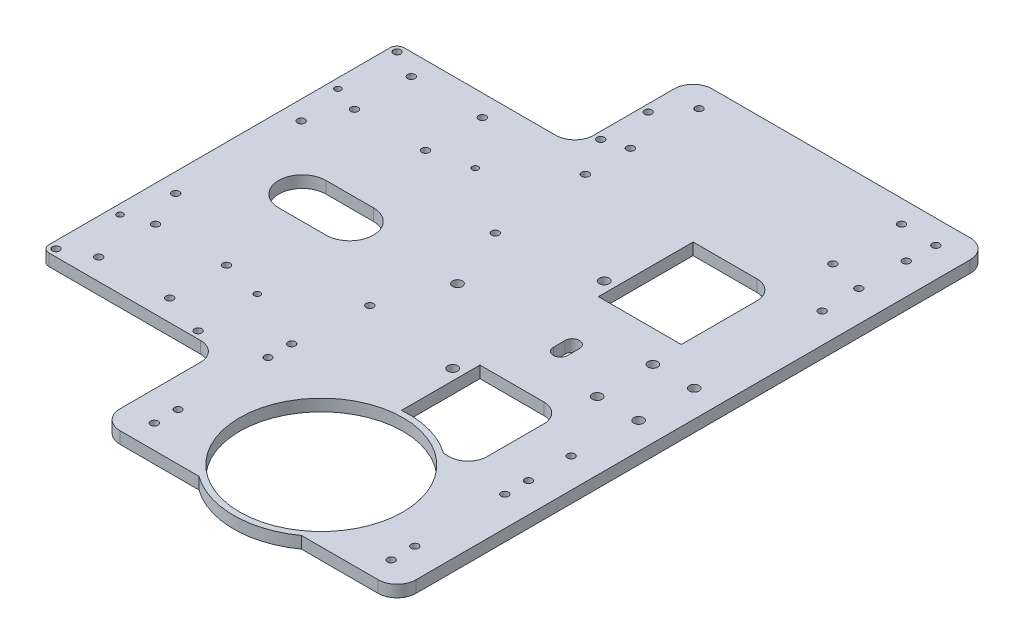
SolidWorks part; units mm, degrees
material "Thornel Mat VMA"
ref_plane "前视基准面" through (0, 0, 0) normal (0, 0, 1) x (1, 0, 0)
ref_plane "上视基准面" through (0, 0, 0) normal (0, 1, 0) x (1, 0, 0)
ref_plane "右视基准面" through (0, 0, 0) normal (1, 0, 0) x (0, 0, -1)
sketch "草图1" plane through (0, 0, 0) normal (0, 1, 0) x (1, 0, 0)
  line L1 (-100, 125) -> (100, 125)
  line L2 (-100, 125) -> (-100, -125)
  line L3 (-100, -125) -> (100, -125)
  line L4 (100, 125) -> (100, -125)
  line L5 (-100, 125) -> (100, -125) construction
  line L6 (-100, -125) -> (100, 125) construction
  point P0 (0, 0)
  dimension "D1" = 200
  dimension "D2" = 250
extrude "凸台-拉伸1" add sketch "草图1" along normal blind 5
ref_plane "基准面1" through (0, 5, 0) normal (0, 1, 0) x (1, 0, 0)
sketch "草图2" plane through (0, 5, 0) normal (0, 1, 0) x (1, 0, 0)
  line L0 (-100, 0) -> (100, 0) construction
  line L1 (-175, 175) -> (-25, 175)
  line L2 (-175, 175) -> (-175, 75)
  line L3 (-175, 75) -> (-25, 75)
  line L4 (-25, 175) -> (-25, 75)
  line L5 (-175, 175) -> (-25, 75) construction
  line L6 (-175, 75) -> (-25, 175) construction
  line L7 (-100, 125) -> (-100, -125) construction
  line L8 (100, -125) -> (100, 125) construction
  line L9 (-175, -75) -> (-25, -75)
  line L10 (-25, -175) -> (-25, -75)
  line L11 (-175, -175) -> (-25, -175)
  line L12 (-175, -175) -> (-175, -75)
  point P0 (-100, 125)
  dimension "D1" = 100
  dimension "D2" = 150
extrude "切除-拉伸1" cut sketch "草图2" against normal blind 10
ref_plane "基准面2" through (0, 5, 0) normal (0, 1, 0) x (1, 0, 0)
ref_plane "基准面3" through (0, 0, 0) normal (0, -1, 0) x (-1, 0, 0)
sketch "草图3" plane through (0, 0, 0) normal (0, -1, 0) x (-1, 0, 0)
  circle A0 centre (85, 66) radius 1.55
  circle A1 centre (55, 66) radius 1.55
  circle A2 centre (55, 42) radius 1.55
  circle A3 centre (85, 42) radius 1.55
  circle A4 centre (55, -42) radius 1.55
  circle A5 centre (85, -42) radius 1.55
  circle A6 centre (55, -66) radius 1.55
  circle A7 centre (85, -66) radius 1.55
extrude "切除-拉伸2" cut sketch "草图3" against normal blind 10
ref_plane "基准面4" through (0, 5, 0) normal (0, 1, 0) x (1, 0, 0)
sketch "草图5" plane through (0, 5, 0) normal (0, 1, 0) x (1, 0, 0)
  line L0 (-70, 97) -> (146, -97) construction
  line L1 (-67.5, 97) -> (-72.5, 97) construction
  line L2 (143.5, -97) -> (148.5, -97) construction
  line L3 (38, 0) -> (-100, 0) construction
  line L4 (-100, 75) -> (-100, -75) construction
ref_plane "基准面5" through (0, 0, 0) normal (0, -1, 0) x (-1, 0, 0)
sketch "草图6" plane through (0, 0, 0) normal (0, -1, 0) x (-1, 0, 0)
  line L5 (-38, 0) -> (100, 0) construction
  line L16 (25, -125) -> (25, -75) construction
  line L17 (-35, -25) -> (-70, -25)
  line L18 (-35, -25) -> (-35, -65)
  line L19 (-35, -65) -> (-70, -65)
  line L20 (-70, -25) -> (-70, -65)
  line L21 (25, -125) -> (-100, -125) construction
  line L22 (-35, 25) -> (-70, 25)
  line L23 (-35, 25) -> (-35, 65)
  line L24 (-35, 65) -> (-70, 65)
  line L25 (-70, 25) -> (-70, 65)
  circle A0 centre (-30.5, 32) radius 2.05
  circle A1 centre (-0.5, 0) radius 2.05
  circle A2 centre (-30.5, -32) radius 2.05
  dimension "D1" = 4.1
  dimension "D2" = 4.1
  dimension "D3" = 4.1
  dimension "D4" = 40
  dimension "D5" = 35
  dimension "D6" = 60
  dimension "D7" = 60
extrude "切除-拉伸3" cut sketch "草图6" against normal blind 5 and the other way blind 10
sketch "草图7" plane through (0, 0, 0) normal (0, -1, 0) x (-1, 0, 0)
  line L0 (-38, 0) -> (-38, -125) construction
  line L1 (70, 97) -> (-146, -97) construction
  line L2 (25, -125) -> (-100, -125) construction
  circle A0 centre (-38, -95) radius 35
  dimension "D1" = 70
  dimension "D2" = 30
extrude "切除-拉伸4" cut sketch "草图7" against normal blind 5
ref_plane "基准面6" through (0, 5, 0) normal (0, 1, 0) x (1, 0, 0)
sketch "草图8" plane through (0, 5, 0) normal (0, 1, 0) x (1, 0, 0)
  circle A0 centre (71.25, 11.75) radius 2.05
  circle A1 centre (88.75, 11.75) radius 2.05
  circle A2 centre (88.75, -11.75) radius 2.05
  circle A3 centre (71.25, -11.75) radius 2.05
extrude "切除-拉伸5" cut sketch "草图8" against normal through all
sketch "草图9" plane through (0, 5, 0) normal (0, 1, 0) x (1, 0, 0)
  circle A0 centre (38, -95) radius 53.0754 construction
sketch "草图10" plane through (0, 5, 0) normal (0, 1, 0) x (1, 0, 0)
  line L0 (-25, -60) -> (100, -60) construction
  line L1 (100, -125) -> (100, 125) construction
  line L2 (-25, -60) -> (-25, -125) construction
  line L4 (-12.5, -67) -> (87.5, -67) construction
  line L5 (-12.5, -67) -> (-12.5, -115) construction
  line L6 (-12.5, -115) -> (87.5, -115) construction
  line L7 (87.5, -67) -> (87.5, -115) construction
  arc A0 (35, -60.1288) -> (19.9722, -125) centre (38, -95) ccw construction
  circle A1 centre (-12.5, -67) radius 1.55
  circle A2 centre (-12.5, -115) radius 1.55
  circle A3 centre (87.5, -67) radius 1.55
  circle A4 centre (87.5, -115) radius 1.55
  dimension "D3" = 3.1
  dimension "D4" = 3.1
  dimension "D5" = 7
  dimension "D2" = 3.1
  dimension "D8" = 3.1
  dimension "D1" = 12.5
  dimension "D6" = 100
  dimension "D7" = 48
extrude "切除-拉伸6" cut sketch "草图10" against normal blind 10
sketch "草图11" plane through (0, 5, 0) normal (0, 1, 0) x (1, 0, 0)
  line L0 (100, -125) -> (100, 125) construction
  line L1 (87.5, 115) -> (-12.5, 115) construction
  line L2 (87.5, 115) -> (87.5, 67) construction
  line L3 (87.5, 67) -> (-12.5, 67) construction
  line L4 (-12.5, 115) -> (-12.5, 67) construction
  line L5 (100, 125) -> (-25, 125) construction
  circle A0 centre (87.5, 115) radius 1.55
  circle A1 centre (87.5, 67) radius 1.55
  circle A2 centre (-12.5, 115) radius 1.55
  circle A3 centre (-12.5, 67) radius 1.55
  dimension "D2" = 3.1
  dimension "D3" = 3.1
  dimension "D4" = 3.1
  dimension "D5" = 3.1
  dimension "D1" = 100
  dimension "D6" = 12.5
  dimension "D7" = 10
extrude "切除-拉伸7" cut sketch "草图11" against normal blind 5
sketch "草图14" plane through (0, 5, 0) normal (0, 1, 0) x (1, 0, 0)
  line L0 (38, 0) -> (-100, 0) construction
  line L1 (-92, 26.5) -> (-10, 26.5) construction
  line L2 (-92, 26.5) -> (-92, -26.5) construction
  line L3 (-92, -26.5) -> (-10, -26.5) construction
  line L4 (-10, 26.5) -> (-10, -26.5) construction
  line L5 (-92, 26.5) -> (-10, -26.5) construction
  line L6 (-92, -26.5) -> (-10, 26.5) construction
  line L7 (-100, 75) -> (-100, -75) construction
  circle A0 centre (-92, -26.5) radius 1.55
  circle A1 centre (-92, 26.5) radius 1.55
  circle A2 centre (-10, 26.5) radius 1.55
  circle A3 centre (-10, -26.5) radius 1.55
  point P0 (-51, 0)
  dimension "D4" = 3.1
  dimension "D5" = 3.1
  dimension "D6" = 3.1
  dimension "D7" = 3.1
  dimension "D1" = 53
  dimension "D2" = 82
  dimension "D3" = 90
extrude "切除-拉伸10" cut sketch "草图14" against normal blind 5
sketch "草图16" plane through (0, 5, 0) normal (0, 1, 0) x (1, 0, 0)
  line L0 (38, 0) -> (-100, 0) construction
  line L1 (-96, 46) -> (-38, 46) construction
  line L2 (-96, 46) -> (-96, -46) construction
  line L3 (-96, -46) -> (-38, -46) construction
  line L4 (-38, 46) -> (-38, -46) construction
  line L5 (-96, 46) -> (-38, -46) construction
  line L6 (-96, -46) -> (-38, 46) construction
  line L7 (-100, 75) -> (-100, -75) construction
  circle A0 centre (-96, 46) radius 1.3
  circle A1 centre (-38, 46) radius 1.3
  circle A2 centre (-38, -46) radius 1.3
  circle A3 centre (-96, -46) radius 1.3
  point P0 (-67, 0)
  dimension "D4" = 2.6
  dimension "D5" = 2.6
  dimension "D6" = 2.6
  dimension "D7" = 2.6
  dimension "D1" = 58
  dimension "D2" = 92
  dimension "D3" = 4
extrude "切除-拉伸11" cut sketch "草图16" against normal blind 5
sketch "草图18" plane through (0, 5, 0) normal (0, 1, 0) x (1, 0, 0)
  line L0 (35, -58.1218) -> (35, -60.1288)
  line L1 (35, -60.1288) -> (35, -25) construction
  line L2 (56.0278, -65) -> (59.8008, -65.1048)
  circle A0 centre (38, -95) radius 34.5
  circle A1 centre (38, -95) radius 37
  dimension "D1" = 74
extrude "凸台-拉伸2" add sketch "草图18" against normal blind 5 contours L2 A1 L0 A0
fillet "圆角1" radius 8 3 edges at (70, 2.5, -65) (70, 2.5, 65) (70, 2.5, 25)
sketch "草图19" plane through (0, 5, 0) normal (0, 1, 0) x (1, 0, 0)
  line L0 (-100, 75) -> (-25, 75) construction
  line L1 (-100, 75) -> (-100, -75) construction
  line L2 (-25, -75) -> (-100, -75) construction
  circle A0 centre (-97, 72) radius 1.55
  circle A1 centre (-97, -72) radius 1.55
  dimension "D1" = 3.1
  dimension "D2" = 3
  dimension "D3" = 3
  dimension "D4" = 3.1
  dimension "D6" = 3
  dimension "D5" = 3
extrude "切除-拉伸12" cut sketch "草图19" against normal blind 10
sketch "草图20" plane through (0, 5, 0) normal (0, 1, 0) x (1, 0, 0)
  line L0 (-25, 75) -> (-25, 125) construction
  line L1 (100, 125) -> (-25, 125) construction
  line L2 (100, -125) -> (100, 125) construction
  circle A0 centre (72.4985, 115.5) radius 1.55
  circle A1 centre (72.5, 86.5) radius 1.55
  circle A2 centre (87, 103) radius 1.55
  circle A3 centre (87, 83) radius 1.55
  circle A4 centre (-22, 103) radius 1.55
  circle A5 centre (-22, 83) radius 1.55
  circle A6 centre (-12.5, 86) radius 1.55
  circle A7 centre (-12.5, 115) radius 1.55 construction
  dimension "D1" = 3.1
  dimension "D2" = 3.1
  dimension "D3" = 3.1
  dimension "D4" = 3.1
  dimension "D5" = 3.1
  dimension "D6" = 3.1
  dimension "D7" = 3.1
  dimension "D8" = 12.5
  dimension "D9" = 29
  dimension "D10" = 3
  dimension "D11" = 22
  dimension "D12" = 3
  dimension "D13" = 20
  dimension "D14" = 13
  dimension "D15" = 22
  dimension "D16" = 13
  dimension "D17" = 20
  dimension "D18" = 9.5
  dimension "D19" = 85
  dimension "D20" = 29
  dimension "D21" = 85
extrude "切除-拉伸13" cut sketch "草图20" against normal blind 10
sketch "草图21" plane through (0, 5, 0) normal (0, 1, 0) x (1, 0, 0)
  line L0 (-65, 0) -> (-45, 0) construction
  line L1 (-65, 10) -> (-45, 10)
  line L2 (-65, -10) -> (-45, -10)
  line L3 (-100, 75) -> (-100, -75) construction
  arc A0 (-65, 10) -> (-65, -10) centre (-65, 0) ccw
  arc A1 (-45, -10) -> (-45, 10) centre (-45, 0) ccw
  point P3 (-55, 0)
  dimension "D2" = 10
  dimension "D3" = 35
  dimension "D1" = 20
extrude "切除-拉伸14" cut sketch "草图21" against normal blind 10
fillet "圆角2" radius 3 2 edges at (-100, 2.5, -75) (-100, 2.5, 75)
fillet "圆角3" radius 8 6 edges at (-25, 2.5, -125) (100, 2.5, -125) (100, 2.5, 125) (-25, 2.5, 125) (-25, 2.5, 75) (-25, 2.5, -75)
sketch "草图22" plane through (0, 0, 0) normal (0, -1, 0) x (-1, 0, 0)
  line L0 (-47, 2) -> (-47, -3) construction
  line L1 (-44, 2) -> (-44, -3)
  line L2 (-50, 2) -> (-50, -3)
  line L3 (-100, -117) -> (-100, 117) construction
  line L4 (-35, -25) -> (-62, -25) construction
  arc A0 (-44, 2) -> (-50, 2) centre (-47, 2) ccw
  arc A1 (-50, -3) -> (-44, -3) centre (-47, -3) ccw
  point P2 (-47, -0.5)
  dimension "D2" = 3
  dimension "D4" = 22
  dimension "D1" = 5
  dimension "D3" = 50
extrude "切除-拉伸15" cut sketch "草图22" against normal blind 10
sketch "草图23" plane through (0, 5, 0) normal (0, 1, 0) x (1, 0, 0)
  line L0 (100, -117) -> (100, 117) construction
  line L1 (59.6564, -125) -> (92, -125) construction
  line L2 (-33, -75) -> (-97, -75) construction
  line L3 (-25, -117) -> (-25, -83) construction
  circle A0 centre (87.5, -39) radius 1.55
  circle A1 centre (-37, -72) radius 1.55
  dimension "D1" = 12.5
  dimension "D2" = 3.1
  dimension "D3" = 86
  dimension "D4" = 3
  dimension "D5" = 3.1
  dimension "D6" = 12
extrude "切除-拉伸16" cut sketch "草图23" against normal blind 10
sketch "草图24" plane through (0, 5, 0) normal (0, 1, 0) x (1, 0, 0)
  line L0 (87.5, -105) -> (87.5, -115) construction
  line L1 (-12.5, -105) -> (-12.5, -115) construction
  circle A0 centre (87.5, -105) radius 1.55
  circle A1 centre (87.5, -115) radius 1.55 construction
  circle A2 centre (-12.5, -105) radius 1.55
  circle A3 centre (87.5, -57) radius 1.55
  circle A4 centre (-12.5, -57) radius 1.55
  point P14 (0, 0)
  point P15 (0, 0)
  dimension "D1" = 3.1
  dimension "D2" = 10
  dimension "D3" = 3.1
  dimension "D4" = 3.1
  dimension "D5" = 48
  dimension "D6" = 3.1
  dimension "D7" = 48
extrude "切除-拉伸17" cut sketch "草图24" against normal blind 10
